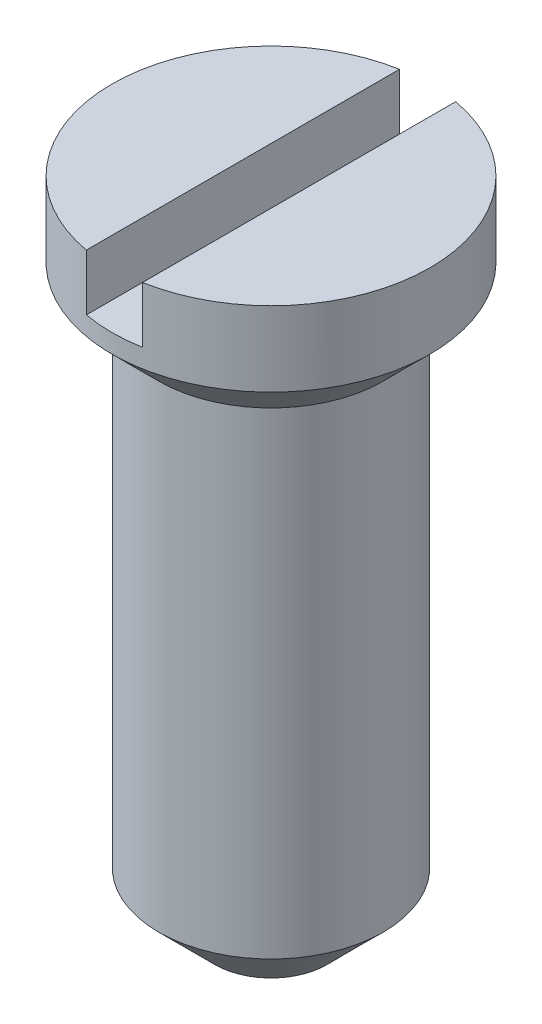
SolidWorks part; units mm, degrees
ref_plane "Front Plane" through (0, 0, 0) normal (0, 0, 1) x (1, 0, 0)
ref_plane "Top Plane" through (0, 0, 0) normal (0, 1, 0) x (1, 0, 0)
ref_plane "Right Plane" through (0, 0, 0) normal (1, 0, 0) x (0, 0, -1)
sketch "Sketch2" plane through (0, 0, 0) normal (0, 1, 0) x (1, 0, 0)
  circle A0 centre (0, 0) radius 0.85
  dimension "D1" = 1.7
extrude "Boss-Extrude1" add sketch "Sketch2" along normal blind 3.5
sketch "Sketch3" plane through (0, 0, 0) normal (0, 0, 1) x (1, 0, 0)
  line L0 (0, 0) -> (0, 3.5) construction
  line L1 (0.85, 3.5) -> (-0.85, 3.5) construction
  line L2 (0.85, 3.1) -> (0.6, 2.85)
  line L3 (0.6, 2.85) -> (0.6, 0)
  line L4 (-0.85, 0) -> (0.85, 0) construction
  line L5 (0.85, 0) -> (0.85, 3.5) construction
  line L6 (0.85, 0) -> (0.85, 3.1)
  line L7 (0.6, 0) -> (0.85, 0)
  dimension "D1" = 1.2
  dimension "D2" = 45
  dimension "D3" = 0.4
revolve "Cut-Revolve1" cut sketch "Sketch3" angle 360 about L0
chamfer "Chamfer1" distance 0.3 angle 45 1 edges at (0, 0, -0.6)
sketch "Sketch4" plane through (0, 3.5, 0) normal (0, 1, 0) x (1, 0, 0)
  line L1 (-0.15, -0.95) -> (0.15, -0.95)
  line L2 (-0.15, -0.95) -> (-0.15, 0.95)
  line L3 (-0.15, 0.95) -> (0.15, 0.95)
  line L4 (0.15, -0.95) -> (0.15, 0.95)
  line L5 (-0.15, -0.95) -> (0.15, 0.95) construction
  line L6 (-0.15, 0.95) -> (0.15, -0.95) construction
  circle A2 centre (0, 0) radius 0.85 construction
  point P0 (0, 0)
  dimension "D1" = 0.3
  dimension "D2" = 0.1
extrude "Cut-Extrude1" cut sketch "Sketch4" against normal blind 0.3
